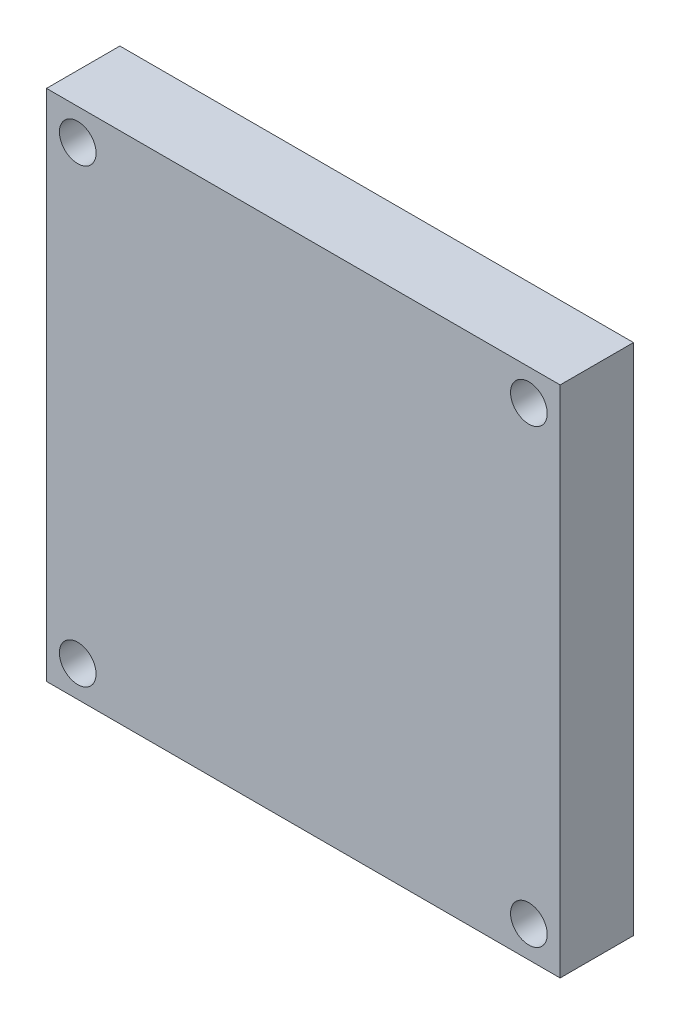
SolidWorks part; units mm, degrees
ref_plane "Alzado" through (0, 0, 0) normal (0, 0, 1) x (1, 0, 0)
ref_plane "Planta" through (0, 0, 0) normal (0, 1, 0) x (1, 0, 0)
ref_plane "Vista lateral" through (0, 0, 0) normal (1, 0, 0) x (0, 0, -1)
sketch "Croquis1" plane through (0, 0, 0) normal (0, 0, 1) x (1, 0, 0)
  line L0 (17.5, -17.5) -> (17.5, -15.37) construction
  line L1 (17.5, -17.5) -> (-17.5, -17.5)
  line L2 (17.5, -17.5) -> (17.5, 17.5)
  line L3 (17.5, 17.5) -> (-17.5, 17.5)
  line L4 (-17.5, -17.5) -> (-17.5, 17.5)
  line L5 (17.5, -17.5) -> (-17.5, 17.5) construction
  line L6 (17.5, 17.5) -> (-17.5, -17.5) construction
  line L7 (17.5, -15.37) -> (15.37, -15.37) construction
  line L8 (-17.5, -15.37) -> (-15.37, -15.37) construction
  line L9 (-15.37, 17.5) -> (-15.37, 15.37) construction
  line L10 (15.37, 17.5) -> (15.37, 15.37) construction
  circle A0 centre (15.37, -15.37) radius 1.25
  circle A1 centre (-15.37, -15.37) radius 1.25
  circle A2 centre (-15.37, 15.37) radius 1.25
  circle A3 centre (15.37, 15.37) radius 1.25
  point P0 (0, 0)
  dimension "D4" = 2.5
  dimension "D6" = 2.5
  dimension "D7" = 2.13
  dimension "D8" = 2.5
  dimension "D10" = 2.5
  dimension "D1" = 35
  dimension "D2" = 2.13
  dimension "D3" = 2.13
  dimension "D5" = 2.13
  dimension "D9" = 2.13
extrude "Saliente-Extruir1" add sketch "Croquis1" along normal blind 5
